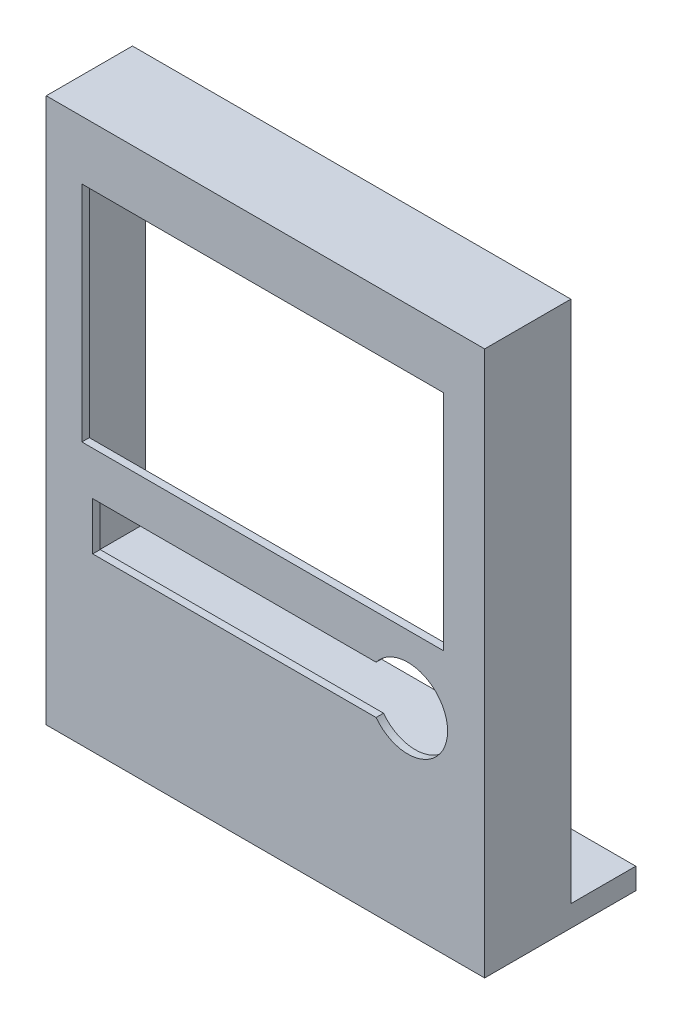
SolidWorks part; units mm, degrees
ref_plane "Front Plane" through (0, 0, 0) normal (0, 0, 1) x (1, 0, 0)
ref_plane "Top Plane" through (0, 0, 0) normal (0, 1, 0) x (1, 0, 0)
ref_plane "Right Plane" through (0, 0, 0) normal (1, 0, 0) x (0, 0, -1)
sketch "Sketch1" plane through (0, 0, 0) normal (0, 0, 1) x (1, 0, 0)
  line L1 (-52.324, -65.024) -> (52.324, -65.024)
  line L2 (-52.324, -65.024) -> (-52.324, 65.024)
  line L3 (-52.324, 65.024) -> (52.324, 65.024)
  line L4 (52.324, -65.024) -> (52.324, 65.024)
  line L5 (-52.324, -65.024) -> (52.324, 65.024) construction
  line L6 (-52.324, 65.024) -> (52.324, -65.024) construction
  point P0 (0, 0)
  dimension "D1" = 130.048
  dimension "D2" = 104.648
extrude "Boss-Extrude1" add sketch "Sketch1" along normal blind 36.068
sketch "Sketch2" plane through (52.324, 0, 0) normal (1, 0, 0) x (0, 0, -1)
  line L0 (-36.068, -65.024) -> (0, -65.024) construction
  line L1 (0, 65.024) -> (-15.494, 65.024)
  line L2 (0, 65.024) -> (0, -59.944)
  line L3 (0, -59.944) -> (-15.494, -59.944)
  line L4 (-15.494, 65.024) -> (-15.494, -59.944)
  dimension "D1" = 15.494
  dimension "D2" = 5.08
extrude "Cut-Extrude1" cut sketch "Sketch2" against normal through all contours L2 L1 L4 L3
sketch "Sketch3" plane through (0, 0, 15.494) normal (0, 0, -1) x (-1, 0, 0)
  line L0 (0, -65.024) -> (0, -32.004)
  line L1 (52.324, -65.024) -> (-52.324, -65.024) construction
  line L2 (-52.324, 65.024) -> (-52.324, -59.944) construction
  line L3 (49.149, -32.004) -> (-49.149, -32.004)
  line L4 (49.149, -32.004) -> (49.149, 61.849)
  line L5 (49.149, 61.849) -> (-49.149, 61.849)
  line L6 (-49.149, -32.004) -> (-49.149, 61.849)
  line L7 (52.324, 65.024) -> (-52.324, 65.024) construction
  line L8 (52.324, 65.024) -> (52.324, -59.944) construction
  dimension "D1" = 33.02
  dimension "D2" = 3.175
  dimension "D3" = 3.175
  dimension "D4" = 3.175
extrude "Cut-Extrude2" cut sketch "Sketch3" against normal blind 18.796 contours L6 L3 L4 L5
sketch "Sketch4" plane through (0, 0, 36.068) normal (0, 0, 1) x (1, 0, 0)
  line L1 (52.324, 65.024) -> (-52.324, 65.024) construction
  line L3 (42.5425, 51.054) -> (-43.8175, 51.054)
  line L4 (42.5425, 51.054) -> (42.5425, -2.286)
  line L5 (42.5425, -2.286) -> (-43.8175, -2.286)
  line L6 (-43.8175, 51.054) -> (-43.8175, -2.286)
  dimension "D2" = 86.36
  dimension "D3" = 53.34
  dimension "D4" = 13.97
extrude "Cut-Extrude3" cut sketch "Sketch4" against normal blind 18.796
sketch "Sketch5" plane through (0, 0, 36.068) normal (0, 0, 1) x (1, 0, 0)
  line L0 (-43.8175, -2.286) -> (42.5425, -2.286) construction
  line L1 (-41.2299, -12.7) -> (40.5581, -12.7)
  line L2 (-41.2299, -12.7) -> (-41.2299, -24.13)
  line L3 (-41.2299, -24.13) -> (40.5581, -24.13)
  line L4 (40.5581, -12.7) -> (40.5581, -24.13)
  circle A0 centre (33.9845, -18.415) radius 9.4904
  dimension "D1" = 10.414
  dimension "D2" = 11.43
  dimension "D3" = 81.788
extrude "Cut-Extrude4" cut sketch "Sketch5" against normal blind 18.796 contours L1 A0 L3 L4 | A0 L1 L2 L3 | L3 A0 L1 L4
sketch "Sketch6" plane through (0, 0, 0) normal (0, 0, -1) x (-1, 0, 0)
  line L1 (-52.324, -59.944) -> (52.324, -59.944)
  line L2 (-52.324, -59.944) -> (-52.324, -65.024)
  line L3 (-52.324, -65.024) -> (52.324, -65.024)
  line L4 (52.324, -59.944) -> (52.324, -65.024)
